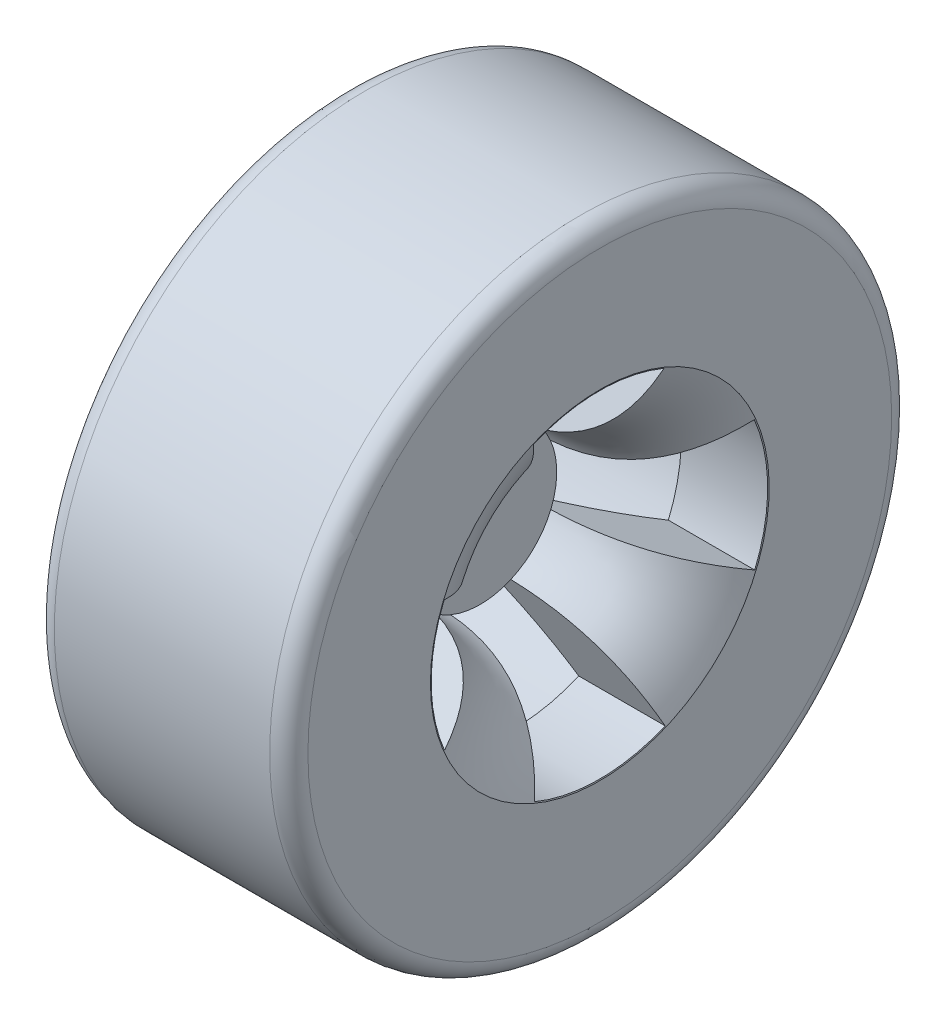
SolidWorks part; units mm, degrees
ref_plane "前视基准面" through (0, 0, 0) normal (0, 0, 1) x (1, 0, 0)
ref_plane "上视基准面" through (0, 0, 0) normal (0, 1, 0) x (1, 0, 0)
ref_plane "右视基准面" through (0, 0, 0) normal (1, 0, 0) x (0, 0, -1)
sketch "草图1" plane through (0, 0, 0) normal (1, 0, 0) x (0, 0, -1)
  circle A0 centre (0, 0) radius 32.5
  dimension "D1" = 65
extrude "凸台-拉伸1" add sketch "草图1" along normal blind 26.5
sketch "草图2" plane through (0, 0, 0) normal (-1, 0, 0) x (0, 0, 1)
  circle A0 centre (0, 0) radius 23
  dimension "D1" = 46
extrude "切除-拉伸1" cut sketch "草图2" against normal blind 26.5
sketch "草图3" plane through (0, 0, 0) normal (0, 0, 1) x (1, 0, 0)
  line L0 (-2, 0) -> (14, 0)
  line L3 (26.5, -32.5) -> (26.5, 32.5) construction
  line L4 (26.5, 0) -> (-2, 0) construction
  line L6 (-2, 5.5) -> (8, 5.5)
  line L7 (8, 5.5) -> (8, 8)
  line L8 (8, 8) -> (14, 8)
  line L15 (-2, 0) -> (-2, 5.5)
  line L16 (-2, 2) -> (8, 2)
  line L17 (14, 8) -> (14, 0)
  line L18 (8, 2) -> (8, 0)
  line L19 (19.206, 23) -> (26.5, 23)
  line L20 (26.5, 23) -> (26.5, 17.6998)
  line L21 (11, 8) -> (14, 8)
  spline S0 degree 2 poles (11, 8) (17.1762, 14.3364) (19.206, 23) knots 0 0 0 1 1 1
  spline S1 degree 2 poles (14, 8) (23.4206, 8.5262) (26.5, 17.6998) knots 0 0 0 1 1 1
  dimension "D2" = 28.5
  dimension "D3" = 5.5
  dimension "D4" = 10
  dimension "D5" = 2.5
  dimension "D6" = 6
  dimension "D10" = 2
revolve "旋转2" add sketch "草图3" angle 360 about L4
sketch "草图4" plane through (26.5, 0, 0) normal (1, 0, 0) x (0, 0, -1)
  line L0 (16.2302, -6.7595) -> (7.378, -3.0928)
  line L1 (16.1835, 6.8705) -> (7.3306, 3.2035)
  line L2 (-6.7595, -16.2302) -> (-3.0928, -7.378)
  line L3 (-6.8705, 16.1835) -> (-3.2035, 7.3306)
  line L4 (6.7595, 16.2302) -> (3.0928, 7.378)
  line L5 (6.8705, -16.1835) -> (3.2035, -7.3306)
  line L6 (-16.2302, 6.7595) -> (-7.378, 3.0928)
  line L7 (-16.1835, -6.8705) -> (-7.3306, -3.2035)
  arc A2 (3.0928, 7.378) -> (-3.2035, 7.3306) centre (0, 0) ccw
  arc A4 (-6.8705, 16.1835) -> (6.7595, 16.2302) centre (0, 0) cw
  arc A5 (7.378, -3.0928) -> (7.3306, 3.2035) centre (0, 0) ccw
  arc A6 (16.1835, 6.8705) -> (16.2302, -6.7595) centre (0, 0) cw
  arc A7 (-3.0928, -7.378) -> (3.2035, -7.3306) centre (0, 0) ccw
  arc A8 (6.8705, -16.1835) -> (-6.7595, -16.2302) centre (0, 0) cw
  arc A9 (-7.378, 3.0928) -> (-7.3306, -3.2035) centre (0, 0) ccw
  arc A10 (-16.1835, -6.8705) -> (-16.2302, 6.7595) centre (0, 0) cw
  point P21 (0, 0)
  dimension "D1" = 4
extrude "切除-拉伸2" cut sketch "草图4" against normal blind 26.5
fillet "圆角1" radius 2 2 edges at (26.5, 0, -32.5) (0, 0, -32.5)
